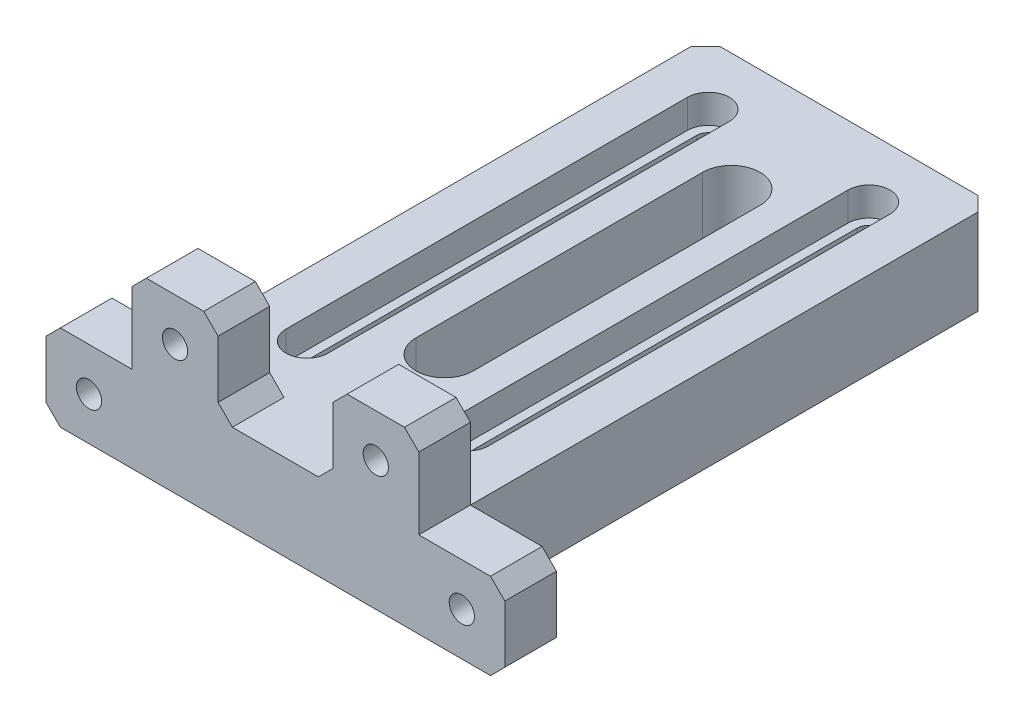
SolidWorks part; units mm, degrees
ref_plane "Front Plane" through (0, 0, 0) normal (0, 0, 1) x (1, 0, 0)
ref_plane "Top Plane" through (0, 0, 0) normal (0, 1, 0) x (1, 0, 0)
ref_plane "Right Plane" through (0, 0, 0) normal (1, 0, 0) x (0, 0, -1)
sketch "Sketch1" plane through (0, 0, 0) normal (0, 0, 1) x (1, 0, 0)
  line L1 (-25, 7.5) -> (25, 7.5)
  line L2 (-25, 7.5) -> (-25, -7.5)
  line L3 (-25, -7.5) -> (25, -7.5)
  line L4 (25, 7.5) -> (25, -7.5)
  line L5 (-25, 7.5) -> (25, -7.5) construction
  line L6 (-25, -7.5) -> (25, 7.5) construction
  line L18 (-17.5, 22.5) -> (-17.5, 7.5) construction
  line L19 (-25, 7.5) -> (-10, 7.5)
  line L20 (-25, 7.5) -> (-25, 22.5)
  line L21 (-25, 22.5) -> (-10, 22.5)
  line L22 (-10, 7.5) -> (-10, 22.5)
  line L37 (-25, -7.5) -> (25, -7.5)
  line L39 (-25, 7.5) -> (-40, 7.5)
  line L40 (-25, 7.5) -> (-25, -7.5)
  line L41 (-25, -7.5) -> (-40, -7.5)
  line L42 (-40, 7.5) -> (-40, -7.5)
  line L43 (-40, 0) -> (-25, 0) construction
  line L44 (0, 7.5) -> (0, -7.5) construction
  line L46 (25, 7.5) -> (10, 7.5)
  line L47 (25, 7.5) -> (25, 22.5)
  line L48 (25, 22.5) -> (10, 22.5)
  line L49 (10, 7.5) -> (10, 22.5)
  line L51 (25, 7.5) -> (40, 7.5)
  line L52 (25, 7.5) -> (25, -7.5)
  line L53 (25, -7.5) -> (40, -7.5)
  line L54 (40, 7.5) -> (40, -7.5)
  line L55 (17.5, 22.5) -> (17.5, 7.5) construction
  line L57 (25, 0) -> (40, 0) construction
  circle A6 centre (-17.5, 15) radius 2.2
  circle A21 centre (-32.5, 0) radius 2.2
  circle A22 centre (17.5, 15) radius 2.2
  circle A23 centre (32.5, 0) radius 2.2
  point P0 (0, 0)
  point P15 (-25, 0)
  dimension "D4" = 15
  dimension "D19" = 4.4
  dimension "D5" = 15
  dimension "D6" = 15
  dimension "D3" = 4.4
  dimension "D9" = 4.4
  dimension "D10" = 4.4
  dimension "D1" = 50
  dimension "D2" = 15
  dimension "D7" = 15
  dimension "D8" = 15
  dimension "D14" = 15
  dimension "D15" = 15
extrude "Boss-Extrude1" add sketch "Sketch1" along normal blind 100
sketch "Sketch5" plane through (0, 0, 0) normal (0, 0, -1) x (-1, 0, 0)
  line L5 (-40, -7.5) -> (40, -7.5) construction
  line L14 (-25, 22.5) -> (25, 22.5)
  line L15 (-25, 22.5) -> (-25, 7.5)
  line L16 (-25, 7.5) -> (25, 7.5)
  line L17 (25, 22.5) -> (25, 7.5)
  line L22 (-40, 7.5) -> (-25, 7.5)
  line L23 (-40, 7.5) -> (-40, -7.5)
  line L24 (-40, -7.5) -> (-25, -7.5)
  line L25 (-25, 7.5) -> (-25, -7.5)
  line L27 (40, -7.5) -> (25, -7.5)
  line L28 (40, -7.5) -> (40, 7.5)
  line L29 (40, 7.5) -> (25, 7.5)
  line L30 (25, -7.5) -> (25, 7.5)
  line M14 (-40, -7.5) -> (40, -7.5)
  line M21 (25, 7.5) -> (25, 22.5)
  line M22 (25, 22.5) -> (10, 22.5)
  line M23 (10, 22.5) -> (10, 7.5)
  circle M38 centre (17.5, 15) radius 2.2
  line M116 (-25, 7.5) -> (-40, 7.5)
  circle M118 centre (32.5, 0) radius 2.2
  line M119 (40, 7.5) -> (25, 7.5)
  line M120 (40, -7.5) -> (40, 7.5)
  line M121 (-10, 7.5) -> (-10, 22.5)
  line M122 (-10, 22.5) -> (-25, 22.5)
  line M123 (-25, 22.5) -> (-25, 7.5)
  line M124 (-40, 7.5) -> (-40, -7.5)
  circle M125 centre (-17.5, 15) radius 2.2
  circle M126 centre (-32.5, 0) radius 2.2
extrude "Cut-Extrude2" cut sketch "Sketch5" against normal offset from surface (91 mm away) 9 contours L25 M116 M124 M14 M126 | L16 M123 M121 M122 M125 | L16 M23 M21 M22 M38 | L30 M14 M120 M119 M118 up to face at (-30.3, 0, 100)
sketch "Sketch6" plane through (0, -7.5, 0) normal (0, -1, 0) x (1, 0, 0)
  line L0 (0, 70.5) -> (0, 20.5) construction
  line L1 (5, 70.5) -> (5, 20.5)
  line L2 (-5, 70.5) -> (-5, 20.5)
  line L3 (-14, 80.5) -> (-14, 10.5) construction
  line L4 (-11.9, 80.5) -> (-11.9, 10.5)
  line L5 (-16.1, 80.5) -> (-16.1, 10.5)
  line L6 (-14, 45.5) -> (0, 45.5) construction
  line L9 (25, 45.5) -> (0, 45.5) construction
  line L12 (0, -16.5) -> (0, 16.5) construction
  line L13 (14, 80.5) -> (14, 10.5) construction
  line L14 (11.9, 80.5) -> (11.9, 10.5)
  line L15 (16.1, 80.5) -> (16.1, 10.5)
  line L17 (25, 91) -> (25, 0) construction
  line L18 (40, 91) -> (25, 91) construction
  arc A0 (5, 70.5) -> (-5, 70.5) centre (0, 70.5) ccw
  arc A1 (-5, 20.5) -> (5, 20.5) centre (0, 20.5) ccw
  arc A2 (-11.9, 80.5) -> (-16.1, 80.5) centre (-14, 80.5) ccw
  arc A3 (-16.1, 10.5) -> (-11.9, 10.5) centre (-14, 10.5) ccw
  arc A4 (11.9, 80.5) -> (16.1, 80.5) centre (14, 80.5) cw
  arc A5 (16.1, 10.5) -> (11.9, 10.5) centre (14, 10.5) cw
  point P2 (0, 45.5)
  point P9 (-14, 45.5)
  point P30 (14, 45.5)
  dimension "D2" = 4.2
  dimension "D1" = 10
  dimension "D3" = 50
  dimension "D4" = 14
  dimension "D6" = 70
extrude "Cut-Extrude3" cut sketch "Sketch6" against normal through all
ref_plane "Plane1" through (0, 15, 0) normal (0, 1, 0) x (1, 0, 0)
sketch "Sketch2" plane through (0, 15, 0) normal (0, 1, 0) x (1, 0, 0)
  line L0 (-17.5, -91) -> (-17.5, -94)
  line L1 (-25, -91) -> (-10, -91) construction
  line L2 (-17.5, -94) -> (-15.3, -94)
  line L3 (-15.3, -94) -> (-12.6921, -91)
  line L4 (-12.6921, -91) -> (-17.5, -91)
  dimension "D1" = 3
  dimension "D2" = 2.2
  dimension "D3" = 131
revolve "Cut-Revolve1" cut sketch "Sketch2" angle 360 about L0
pattern_linear "LPattern1" count 2 spacing 35 along (1, 0, 0) of "Cut-Revolve1"
ref_plane "Plane2" through (-32.5, 0, 0) normal (-1, 0, 0) x (0, 0, 1)
sketch "Sketch8" plane through (-32.5, 0, 0) normal (-1, 0, 0) x (0, 0, 1)
  line L0 (91, 0) -> (94, 0)
  line L1 (91, -7.5) -> (91, 7.5) construction
  line L2 (94, 0) -> (94, 2.2)
  line L3 (94, 2.2) -> (91, 4.8079)
  line L4 (91, -7.5) -> (91, 7.5) construction
  line L5 (91, 4.8079) -> (91, 0)
  dimension "D1" = 3
  dimension "D2" = 2.2
  dimension "D3" = 131
revolve "Cut-Revolve2" cut sketch "Sketch8" angle 360 about L0
mirror "Mirror3" about plane through (0, 0, 0) normal (1, 0, 0) of "Cut-Revolve2"
sketch "Sketch7" plane through (0, 7.5, 0) normal (0, 1, 0) x (1, 0, 0)
  line L0 (-16.1, -45.5) -> (-11.9, -45.5) construction
  line L3 (-14, -10.5) -> (-14, -80.5) construction
  line L4 (-10.35, -10.5) -> (-10.35, -80.5)
  line L5 (-17.65, -10.5) -> (-17.65, -80.5)
  line L6 (0, -16.5) -> (0, 16.5) construction
  line L7 (14, -10.5) -> (14, -80.5) construction
  line L8 (10.35, -10.5) -> (10.35, -80.5)
  line L9 (17.65, -10.5) -> (17.65, -80.5)
  line L10 (-16.1, -10.5) -> (-16.1, -80.5) construction
  arc A0 (-10.35, -10.5) -> (-17.65, -10.5) centre (-14, -10.5) ccw
  arc A1 (-17.65, -80.5) -> (-10.35, -80.5) centre (-14, -80.5) ccw
  arc A2 (10.35, -10.5) -> (17.65, -10.5) centre (14, -10.5) cw
  arc A3 (17.65, -80.5) -> (10.35, -80.5) centre (14, -80.5) cw
  point P8 (-14, -45.5)
  point P22 (14, -45.5)
  dimension "D1" = 3.65
extrude "Cut-Extrude4" cut sketch "Sketch7" against normal blind 5
chamfer "Chamfer1" distance 2.5 angle 45 12 edges at (-25, 0, 0) (25, 0, 0) (-25, 22.5, 95.5) (-10, 22.5, 95.5) (-10, 7.5, 95.5) (10, 7.5, 95.5) (10, 22.5, 95.5) (25, 22.5, 95.5) (40, 7.5, 95.5) (40, -7.5, 95.5) (-40, -7.5, 95.5) (-40, 7.5, 95.5)
